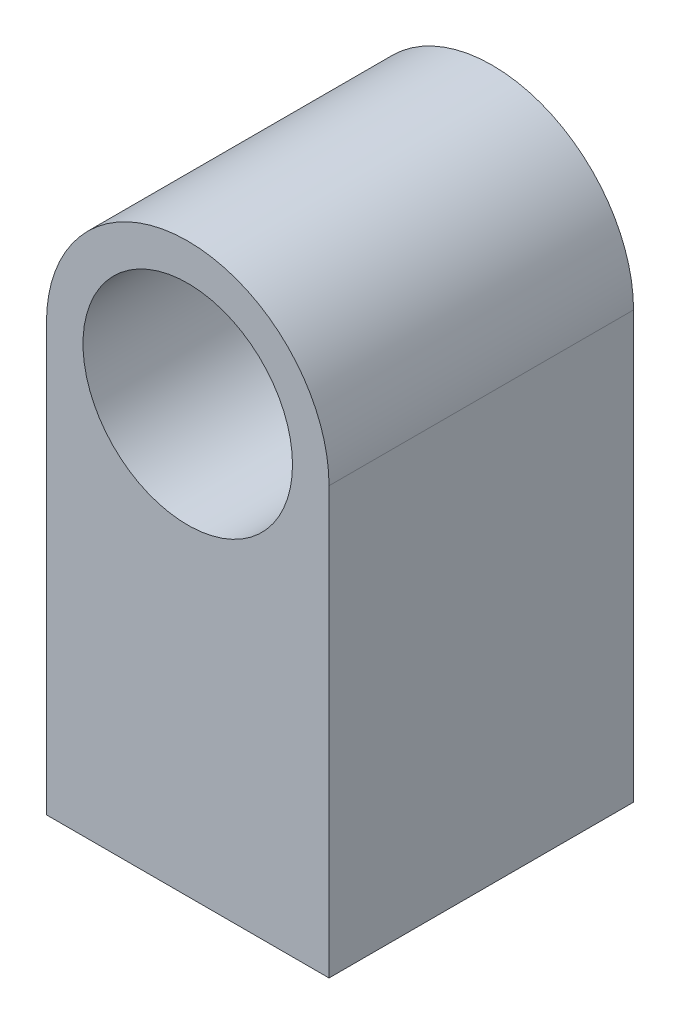
SolidWorks part; units mm, degrees
ref_plane "Alzado" through (0, 0, 0) normal (0, 0, 1) x (1, 0, 0)
ref_plane "Planta" through (0, 0, 0) normal (0, 1, 0) x (1, 0, 0)
ref_plane "Vista lateral" through (0, 0, 0) normal (1, 0, 0) x (0, 0, -1)
sketch "Croquis1" plane through (0, 0, 0) normal (0, 0, 1) x (1, 0, 0)
  line L0 (0, 0) -> (0, -10) construction
  line L1 (-11.6, -10) -> (11.6, -10)
  line L2 (-11.6, -10) -> (-11.6, 0)
  line L3 (11.6, -10) -> (11.6, 0)
  circle A0 centre (0, 0) radius 8.6
  arc A1 (11.6, 0) -> (-11.6, 0) centre (0, 0) ccw
  point P8 (0, -10)
  dimension "D1" = 17.2
  dimension "D2" = 3
  dimension "D3" = 10
extrude "Saliente-Extruir1" add sketch "Croquis1" against normal mid plane 25
ref_plane "Plano1" through (0, -10, 0) normal (0, -1, 0) x (-1, 0, 0)
sketch "Croquis3" plane through (0, -10, 0) normal (0, -1, 0) x (-1, 0, 0)
  line L0 (11.6, -12.5) -> (-11.6, -12.5) construction
  line L1 (11.6, 12.5) -> (11.6, -12.5) construction
  line L2 (-11.6, 12.5) -> (-11.6, -12.5) construction
  line L3 (11.6, 12.5) -> (-11.6, 12.5) construction
  line L4 (11.6, -12.5) -> (-11.6, -12.5)
  line L5 (11.6, 12.5) -> (11.6, -12.5)
  line L6 (-11.6, 12.5) -> (-11.6, -12.5)
  line L7 (11.6, 12.5) -> (-11.6, 12.5)
  circle A0 centre (0, 0) radius 8.6
  dimension "D1" = 17.2
extrude "Saliente-Extruir2" add sketch "Croquis3" along normal blind 25
